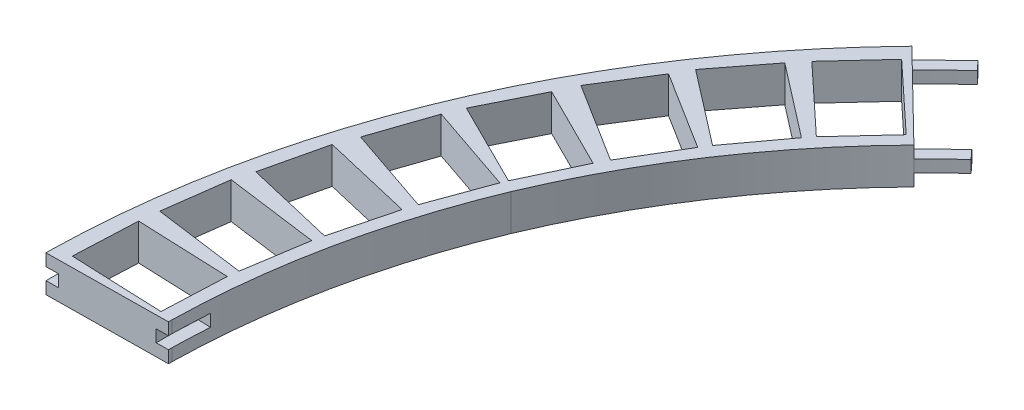
SolidWorks part; units mm, degrees
ref_plane "Front Plane" through (0, 0, 0) normal (0, 0, 1) x (1, 0, 0)
ref_plane "Top Plane" through (0, 0, 0) normal (0, 1, 0) x (1, 0, 0)
ref_plane "Right Plane" through (0, 0, 0) normal (1, 0, 0) x (0, 0, -1)
sketch "Sketch1" plane through (0, 0, 0) normal (0, 1, 0) x (1, 0, 0)
  line L0 (0, -1585.8629) -> (0, 77707.2829) construction
  line L1 (-1585.8629, 0) -> (77707.2829, 0) construction
  line L3 (-211.1748, 206.2011) -> (-182.565, 178.2651)
  line L38 (0, 0) -> (-235.7776, 98.424) construction
  line L40 (-288.8539, 28.4755) -> (-289.7958, 7.4966)
  line L41 (-258.3558, 27.2479) -> (-288.8539, 28.4755)
  line L42 (-259.2977, 6.269) -> (-258.3558, 27.2479)
  line L43 (-288.203, 34.7844) -> (-257.9496, 30.7242)
  line L44 (-285.408, 55.5976) -> (-288.203, 34.7844)
  line L45 (-254.6834, 51.4742) -> (-285.408, 55.5976)
  line L46 (-257.9496, 30.7242) -> (-254.6834, 51.4742)
  line L47 (-283.6129, 61.9158) -> (-253.8994, 54.9336)
  line L48 (-278.809, 82.359) -> (-283.6129, 61.9158)
  line L49 (-248.631, 75.2676) -> (-278.809, 82.359)
  line L50 (-253.8994, 54.9336) -> (-248.631, 75.2676)
  line L51 (-276.2559, 89.1768) -> (-247.3613, 79.3409)
  line L52 (-269.4887, 109.0566) -> (-276.2559, 89.1768)
  line L53 (-240.1424, 99.0668) -> (-269.4887, 109.0566)
  line L54 (-247.3613, 79.3409) -> (-240.1424, 99.0668)
  line L58 (-295.0857, 6.177) -> (-295.0857, 4.0924)
  line L60 (-255.1043, 5.7001) -> (-255.1043, 4.5689)
  line L61 (-289.7958, 7.4966) -> (-259.2977, 6.269)
  line L66 (-255.1043, 4.5689) -> (-295.0857, 4.0924)
  line L79 (-230.3553, 120.0793) -> (-239.3039, 101.0754)
  line L80 (-239.3039, 101.0754) -> (-267.0429, 114.9156)
  line L81 (-267.0429, 114.9156) -> (-257.6673, 133.7065)
  line L82 (-257.6673, 133.7065) -> (-230.3553, 120.0793)
  line L83 (-217.5995, 141.891) -> (-228.3521, 123.8463)
  line L84 (-228.3521, 123.8463) -> (-254.6152, 140.316)
  line L85 (-254.6152, 140.316) -> (-243.4584, 158.1071)
  line L86 (-243.4584, 158.1071) -> (-217.5995, 141.891)
  line L87 (-203.235, 161.7947) -> (-215.6912, 144.8811)
  line L88 (-215.6912, 144.8811) -> (-240.2284, 163.8264)
  line L89 (-240.2284, 163.8264) -> (-227.3959, 180.4495)
  line L90 (-227.3959, 180.4495) -> (-203.235, 161.7947)
  line L91 (-186.7955, 179.9501) -> (-201.049, 164.5281)
  line L92 (-201.049, 164.5281) -> (-223.3681, 185.3487)
  line L93 (-223.3681, 185.3487) -> (-209.1146, 200.7708)
  line L94 (-209.1146, 200.7708) -> (-186.7955, 179.9501)
  arc A0 (-259.7741, 0) -> (-185.8638, 181.4863) centre (0, 0) ccw construction
  arc A1 (-295.0857, 6.177) -> (-211.1748, 206.2011) centre (0, 0) cw
  arc A3 (-259.7741, 0) -> (-185.8638, 181.4863) centre (0, 0) ccw construction
  arc A4 (-259.7741, 0) -> (-185.8638, 181.4863) centre (0, 0) ccw construction
  arc A5 (-259.7741, 0) -> (-185.8638, 181.4863) centre (0, 0) ccw construction
  arc A6 (-259.7741, 0) -> (-185.8638, 181.4863) centre (0, 0) ccw construction
  arc A7 (-259.7741, 0) -> (-185.8638, 181.4863) centre (0, 0) ccw construction
  arc A8 (-259.7741, 0) -> (-185.8638, 181.4863) centre (0, 0) ccw construction
  arc A9 (-259.7741, 0) -> (-185.8638, 181.4863) centre (0, 0) ccw construction
  arc A12 (-259.7741, 0) -> (-185.8638, 181.4863) centre (0, 0) ccw construction
  arc A13 (-259.7741, 0) -> (-185.8638, 181.4863) centre (0, 0) ccw construction
  arc A14 (-259.7741, 0) -> (-185.8638, 181.4863) centre (0, 0) ccw construction
  arc A15 (-259.7741, 0) -> (-185.8638, 181.4863) centre (0, 0) ccw construction
  arc A16 (-259.7741, 0) -> (-185.8638, 181.4863) centre (0, 0) ccw construction
  arc A17 (-259.7741, 0) -> (-185.8638, 181.4863) centre (0, 0) ccw construction
  arc A18 (-259.7741, 0) -> (-185.8638, 181.4863) centre (0, 0) ccw construction
  arc A20 (-235.7776, 98.424) -> (-182.565, 178.2651) centre (-0.616, -0.6536) cw
  arc A21 (-235.7776, 98.424) -> (-255.1043, 5.7001) centre (0.0316, 0.8976) ccw
  dimension "D2" = 45
  dimension "D3" = 1.75
  dimension "D6" = 1.75
  dimension "D7" = 3.5
  dimension "D8" = 3.5472
  dimension "D9" = 3.5
  dimension "D4" = 21
  dimension "D5" = 21
  dimension "D10" = 3.5472
  dimension "D11" = 8
  dimension "D18" = 8
extrude "Boss-Extrude1" add sketch "Sketch1" along normal blind 12
sketch "Sketch3" plane through (-0.0907, 0, -7.6077) normal (0.0119, 0, 0.9999) x (0.9999, 0, -0.0119)
  line L1 (-254.6317, 4.0201) -> (-259.0317, 4.0201)
  line L2 (-254.6317, 4.0201) -> (-254.6317, 8.0201)
  line L3 (-254.6317, 8.0201) -> (-259.0317, 8.0201)
  line L4 (-259.0317, 4.0201) -> (-259.0317, 8.0201)
  line L5 (-275.0238, 12) -> (-275.0238, 0) construction
  line L6 (-295.016, 12) -> (-255.0317, 12) construction
  line L7 (-295.016, 0) -> (-255.0317, 0) construction
  line L8 (-295.416, 8.0201) -> (-291.016, 8.0201)
  line L9 (-291.016, 4.0201) -> (-291.016, 8.0201)
  line L10 (-295.416, 4.0201) -> (-291.016, 4.0201)
  line L11 (-295.416, 4.0201) -> (-295.416, 8.0201)
  line L12 (0, 0) -> (0, 37.9372) construction
  line L13 (-255.0317, 12) -> (-255.0317, 0) construction
  point P21 (0, 0)
  dimension "D1" = 4
  dimension "D2" = 4
  dimension "D3" = 4.0399
  dimension "D4" = 4.4
  dimension "D5" = 0.4
revolve "Cut-Revolve1" cut sketch "Sketch3" angle 3 about L12
sketch "Sketch4" plane through (0, 0, 0) normal (0.6986, 0, -0.7155) x (-0.7155, 0, -0.6986)
  line L0 (255.1635, 12) -> (255.1635, 0) construction
  line L1 (255.1635, 8) -> (259.1635, 8)
  line L2 (255.1635, 8) -> (255.1635, 4)
  line L3 (255.1635, 4) -> (259.1635, 4)
  line L4 (259.1635, 8) -> (259.1635, 4)
  line L5 (275.1569, 12) -> (275.1569, 0) construction
  line L6 (255.1635, 12) -> (295.1503, 12) construction
  line L7 (255.1635, 0) -> (295.1503, 0) construction
  line L8 (295.1503, 4) -> (291.1503, 4)
  line L9 (291.1503, 8) -> (291.1503, 4)
  line L10 (295.1503, 8) -> (291.1503, 8)
  line L11 (295.1503, 8) -> (295.1503, 4)
  line L12 (0, 0) -> (0, 5.1403) construction
  dimension "D1" = 4
  dimension "D2" = 4
  dimension "D3" = 4
revolve "Revolve1" add sketch "Sketch4" angle 3 about L12
